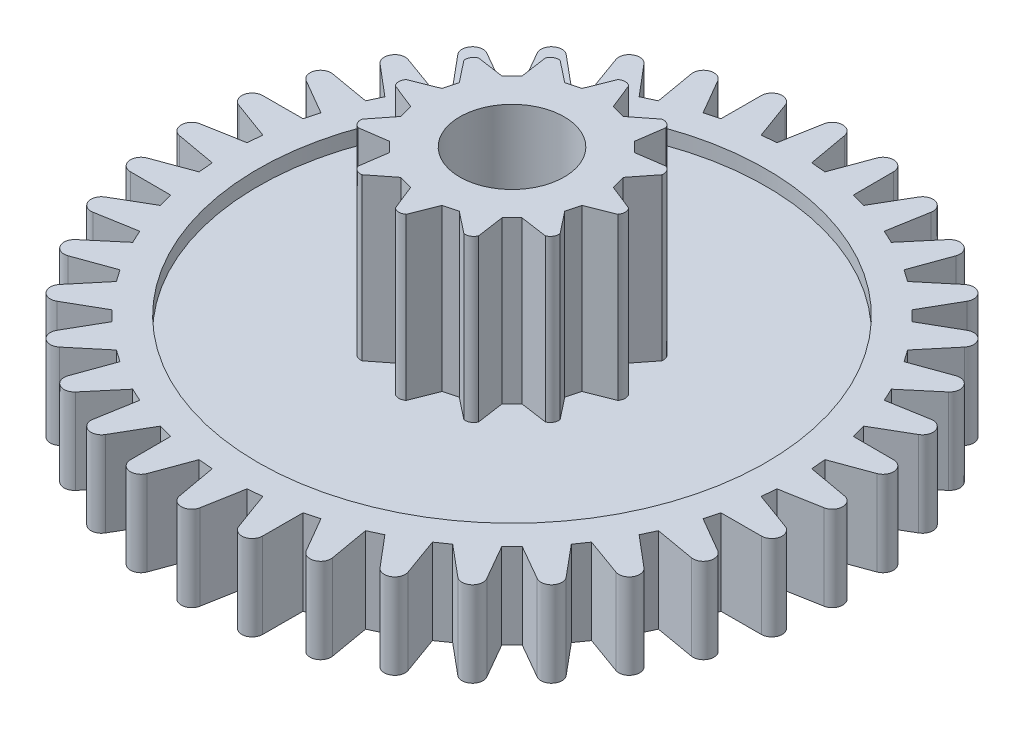
SolidWorks part; units mm, degrees
material "ABS"
ref_plane "Plano frontal" through (0, 0, 0) normal (0, 0, 1) x (1, 0, 0)
ref_plane "Plano superior" through (0, 0, 0) normal (0, 1, 0) x (1, 0, 0)
ref_plane "Plano direito" through (0, 0, 0) normal (1, 0, 0) x (0, 0, -1)
ref_plane "Plano1" through (0, -1.225, 0) normal (0, -1, 0) x (1, 0, 0)
sketch "Esboço1" plane through (0, -1.225, 0) normal (0, -1, 0) x (1, 0, 0)
  line L0 (-0.5, -8.1096) -> (-0.2953, -9.2529)
  line L1 (0.2953, -9.2529) -> (0.5, -8.1096)
  line L2 (0.5, -8.1096) -> (0.9158, -8.0732)
  line L3 (0.9158, -8.0732) -> (1.3159, -9.1636)
  line L4 (1.8976, -9.061) -> (1.9006, -7.8996)
  line L5 (1.9006, -7.8996) -> (2.3673, -7.9008)
  line L6 (2.3673, -7.9008) -> (2.8872, -8.7959)
  line L7 (3.4422, -8.5939) -> (3.2435, -7.4495)
  line L8 (3.2435, -7.4495) -> (3.6218, -7.2731)
  line L9 (3.6218, -7.2731) -> (4.3707, -8.1609)
  line L10 (4.8822, -7.8656) -> (4.4878, -6.7731)
  line L11 (4.4878, -6.7731) -> (4.8297, -6.5337)
  line L12 (4.8297, -6.5337) -> (5.7214, -7.2779)
  line L13 (6.1738, -6.8983) -> (5.5958, -5.8909)
  line L14 (5.5958, -5.8909) -> (5.8909, -5.5958)
  line L15 (5.8909, -5.5958) -> (6.8983, -6.1738)
  line L16 (7.2779, -5.7214) -> (6.5337, -4.8297)
  line L17 (6.5337, -4.8297) -> (6.7731, -4.4878)
  line L18 (6.7731, -4.4878) -> (7.8656, -4.8822)
  line L19 (8.1609, -4.3707) -> (7.2731, -3.6218)
  line L20 (7.2731, -3.6218) -> (7.4495, -3.2435)
  line L21 (7.4495, -3.2435) -> (8.5939, -3.4422)
  line L22 (8.7959, -2.8872) -> (7.9008, -2.3673)
  line L23 (7.9008, -2.3673) -> (7.8996, -1.9006)
  line L24 (7.8996, -1.9006) -> (9.061, -1.8976)
  line L25 (9.1636, -1.3159) -> (8.0732, -0.9158)
  line L26 (8.0732, -0.9158) -> (8.1096, -0.5)
  line L27 (8.1096, -0.5) -> (9.2529, -0.2953)
  line L28 (9.2529, 0.2953) -> (8.1096, 0.5)
  line L29 (8.1096, 0.5) -> (8.0732, 0.9158)
  line L30 (8.0732, 0.9158) -> (9.1636, 1.3159)
  line L31 (9.061, 1.8976) -> (7.8996, 1.9006)
  line L32 (7.8996, 1.9006) -> (7.9008, 2.3673)
  line L33 (7.9008, 2.3673) -> (8.7959, 2.8872)
  line L34 (8.5939, 3.4422) -> (7.4495, 3.2435)
  line L35 (7.4495, 3.2435) -> (7.2731, 3.6218)
  line L36 (7.2731, 3.6218) -> (8.1609, 4.3707)
  line L37 (7.8656, 4.8822) -> (6.7731, 4.4878)
  line L38 (6.7731, 4.4878) -> (6.5337, 4.8297)
  line L39 (6.5337, 4.8297) -> (7.2779, 5.7214)
  line L40 (6.8983, 6.1738) -> (5.8909, 5.5958)
  line L41 (5.8909, 5.5958) -> (5.5958, 5.8909)
  line L42 (5.5958, 5.8909) -> (6.1738, 6.8983)
  line L43 (5.7214, 7.2779) -> (4.8297, 6.5337)
  line L44 (4.8297, 6.5337) -> (4.4878, 6.7731)
  line L45 (4.4878, 6.7731) -> (4.8822, 7.8656)
  line L46 (4.3707, 8.1609) -> (3.6218, 7.2731)
  line L47 (3.6218, 7.2731) -> (3.2435, 7.4495)
  line L48 (3.2435, 7.4495) -> (3.4422, 8.5939)
  line L49 (2.8872, 8.7959) -> (2.3673, 7.9008)
  line L50 (2.3673, 7.9008) -> (1.9006, 7.8996)
  line L51 (1.9006, 7.8996) -> (1.8976, 9.061)
  line L52 (1.3159, 9.1636) -> (0.9158, 8.0732)
  line L53 (0.9158, 8.0732) -> (0.5, 8.1096)
  line L54 (0.5, 8.1096) -> (0.2953, 9.2529)
  line L55 (-0.2953, 9.2529) -> (-0.5, 8.1096)
  line L56 (-0.5, 8.1096) -> (-0.9158, 8.0732)
  line L57 (-0.9158, 8.0732) -> (-1.3159, 9.1636)
  line L58 (-1.8976, 9.061) -> (-1.9006, 7.8996)
  line L59 (-1.9006, 7.8996) -> (-2.3673, 7.9008)
  line L60 (-2.3673, 7.9008) -> (-2.8872, 8.7959)
  line L61 (-3.4422, 8.5939) -> (-3.2435, 7.4495)
  line L62 (-3.2435, 7.4495) -> (-3.6218, 7.2731)
  line L63 (-3.6218, 7.2731) -> (-4.3707, 8.1609)
  line L64 (-4.8822, 7.8656) -> (-4.4878, 6.7731)
  line L65 (-4.4878, 6.7731) -> (-4.8297, 6.5337)
  line L66 (-4.8297, 6.5337) -> (-5.7214, 7.2779)
  line L67 (-6.1738, 6.8983) -> (-5.5958, 5.8909)
  line L68 (-5.5958, 5.8909) -> (-5.8909, 5.5958)
  line L69 (-5.8909, 5.5958) -> (-6.8983, 6.1738)
  line L70 (-7.2779, 5.7214) -> (-6.5337, 4.8297)
  line L71 (-6.5337, 4.8297) -> (-6.7731, 4.4878)
  line L72 (-6.7731, 4.4878) -> (-7.8656, 4.8822)
  line L73 (-8.1609, 4.3707) -> (-7.2731, 3.6218)
  line L74 (-7.2731, 3.6218) -> (-7.4495, 3.2435)
  line L75 (-7.4495, 3.2435) -> (-8.5939, 3.4422)
  line L76 (-8.7959, 2.8872) -> (-7.9008, 2.3673)
  line L77 (-7.9008, 2.3673) -> (-7.8996, 1.9006)
  line L78 (-7.8996, 1.9006) -> (-9.061, 1.8976)
  line L79 (-9.1636, 1.3159) -> (-8.0732, 0.9158)
  line L80 (-8.0732, 0.9158) -> (-8.1096, 0.5)
  line L81 (-8.1096, 0.5) -> (-9.2529, 0.2953)
  line L82 (-9.2529, -0.2953) -> (-8.1096, -0.5)
  line L83 (-8.1096, -0.5) -> (-8.0732, -0.9158)
  line L84 (-8.0732, -0.9158) -> (-9.1636, -1.3159)
  line L85 (-9.061, -1.8976) -> (-7.8996, -1.9006)
  line L86 (-7.8996, -1.9006) -> (-7.9008, -2.3673)
  line L87 (-7.9008, -2.3673) -> (-8.7959, -2.8872)
  line L88 (-8.5939, -3.4422) -> (-7.4495, -3.2435)
  line L89 (-7.4495, -3.2435) -> (-7.2731, -3.6218)
  line L90 (-7.2731, -3.6218) -> (-8.1609, -4.3707)
  line L91 (-7.8656, -4.8822) -> (-6.7731, -4.4878)
  line L92 (-6.7731, -4.4878) -> (-6.5337, -4.8297)
  line L93 (-6.5337, -4.8297) -> (-7.2779, -5.7214)
  line L94 (-6.8983, -6.1738) -> (-5.8909, -5.5958)
  line L95 (-5.8909, -5.5958) -> (-5.5958, -5.8909)
  line L96 (-5.5958, -5.8909) -> (-6.1738, -6.8983)
  line L97 (-5.7214, -7.2779) -> (-4.8297, -6.5337)
  line L98 (-4.8297, -6.5337) -> (-4.4878, -6.7731)
  line L99 (-4.4878, -6.7731) -> (-4.8822, -7.8656)
  line L100 (-4.3707, -8.1609) -> (-3.6218, -7.2731)
  line L101 (-3.6218, -7.2731) -> (-3.2435, -7.4495)
  line L102 (-3.2435, -7.4495) -> (-3.4422, -8.5939)
  line L103 (-2.8872, -8.7959) -> (-2.3673, -7.9008)
  line L104 (-2.3673, -7.9008) -> (-1.9006, -7.8996)
  line L105 (-1.9006, -7.8996) -> (-1.8976, -9.061)
  line L106 (-1.3159, -9.1636) -> (-0.9158, -8.0732)
  line L107 (-0.9158, -8.0732) -> (-0.5, -8.1096)
  arc A0 (-0.2953, -9.2529) -> (0.2953, -9.2529) centre (0, -9.2) ccw
  arc A1 (1.3159, -9.1636) -> (1.8976, -9.061) centre (1.5976, -9.0602) ccw
  arc A2 (2.8872, -8.7959) -> (3.4422, -8.5939) centre (3.1466, -8.6452) ccw
  arc A3 (4.3707, -8.1609) -> (4.8822, -7.8656) centre (4.6, -7.9674) ccw
  arc A4 (5.7214, -7.2779) -> (6.1738, -6.8983) centre (5.9136, -7.0476) ccw
  arc A5 (6.8983, -6.1738) -> (7.2779, -5.7214) centre (7.0476, -5.9136) ccw
  arc A6 (7.8656, -4.8822) -> (8.1609, -4.3707) centre (7.9674, -4.6) ccw
  arc A7 (8.5939, -3.4422) -> (8.7959, -2.8872) centre (8.6452, -3.1466) ccw
  arc A8 (9.061, -1.8976) -> (9.1636, -1.3159) centre (9.0602, -1.5976) ccw
  arc A9 (9.2529, -0.2953) -> (9.2529, 0.2953) centre (9.2, 0) ccw
  arc A10 (9.1636, 1.3159) -> (9.061, 1.8976) centre (9.0602, 1.5976) ccw
  arc A11 (8.7959, 2.8872) -> (8.5939, 3.4422) centre (8.6452, 3.1466) ccw
  arc A12 (8.1609, 4.3707) -> (7.8656, 4.8822) centre (7.9674, 4.6) ccw
  arc A13 (7.2779, 5.7214) -> (6.8983, 6.1738) centre (7.0476, 5.9136) ccw
  arc A14 (6.1738, 6.8983) -> (5.7214, 7.2779) centre (5.9136, 7.0476) ccw
  arc A15 (4.8822, 7.8656) -> (4.3707, 8.1609) centre (4.6, 7.9674) ccw
  arc A16 (3.4422, 8.5939) -> (2.8872, 8.7959) centre (3.1466, 8.6452) ccw
  arc A17 (1.8976, 9.061) -> (1.3159, 9.1636) centre (1.5976, 9.0602) ccw
  arc A18 (0.2953, 9.2529) -> (-0.2953, 9.2529) centre (0, 9.2) ccw
  arc A19 (-1.3159, 9.1636) -> (-1.8976, 9.061) centre (-1.5976, 9.0602) ccw
  arc A20 (-2.8872, 8.7959) -> (-3.4422, 8.5939) centre (-3.1466, 8.6452) ccw
  arc A21 (-4.3707, 8.1609) -> (-4.8822, 7.8656) centre (-4.6, 7.9674) ccw
  arc A22 (-5.7214, 7.2779) -> (-6.1738, 6.8983) centre (-5.9136, 7.0476) ccw
  arc A23 (-6.8983, 6.1738) -> (-7.2779, 5.7214) centre (-7.0476, 5.9136) ccw
  arc A24 (-7.8656, 4.8822) -> (-8.1609, 4.3707) centre (-7.9674, 4.6) ccw
  arc A25 (-8.5939, 3.4422) -> (-8.7959, 2.8872) centre (-8.6452, 3.1466) ccw
  arc A26 (-9.061, 1.8976) -> (-9.1636, 1.3159) centre (-9.0602, 1.5976) ccw
  arc A27 (-9.2529, 0.2953) -> (-9.2529, -0.2953) centre (-9.2, 0) ccw
  arc A28 (-9.1636, -1.3159) -> (-9.061, -1.8976) centre (-9.0602, -1.5976) ccw
  arc A29 (-8.7959, -2.8872) -> (-8.5939, -3.4422) centre (-8.6452, -3.1466) ccw
  arc A30 (-8.1609, -4.3707) -> (-7.8656, -4.8822) centre (-7.9674, -4.6) ccw
  arc A31 (-7.2779, -5.7214) -> (-6.8983, -6.1738) centre (-7.0476, -5.9136) ccw
  arc A32 (-6.1738, -6.8983) -> (-5.7214, -7.2779) centre (-5.9136, -7.0476) ccw
  arc A33 (-4.8822, -7.8656) -> (-4.3707, -8.1609) centre (-4.6, -7.9674) ccw
  arc A34 (-3.4422, -8.5939) -> (-2.8872, -8.7959) centre (-3.1466, -8.6452) ccw
  arc A35 (-1.8976, -9.061) -> (-1.3159, -9.1636) centre (-1.5976, -9.0602) ccw
extrude "Ressalto-extrusão1" add sketch "Esboço1" against normal blind 2.45
hole_wizard "Furo com folga de M121" positions "Esboço3" profile "Esboço2" hole size "M12" standard "Ansi Metric"
sketch "Esboço3" plane through (0, 1.225, 0) normal (0, 1, 0) x (1, 0, 0)
  point P0 (0, 0)
sketch "Esboço2" plane through (0, 1.225, 0) normal (1, 0, 0) x (0, 0, 1)
  line L0 (0, 0) -> (0, 0.43)
  line L1 (0, 0.43) -> (7.3, 0.43)
  line L2 (7.3, 0.43) -> (7.3, 0)
  line L5 (7.3, 0) -> (0, 0)
  line L10 (0, 0.43) -> (-7.3, 0.43) construction
  line L11 (0, -6.35) -> (0, 107.95) construction
  dimension "Hole Dia." = 14.6
  dimension "Hole Depth" = 0.43
  dimension "Drill Angle" = 180
sketch "Esboço4" plane through (0, 0.795, 0) normal (0, 1, 0) x (-1, 0, 0)
  line L0 (-0.1557, -3.1956) -> (-0.5751, -2.1462)
  line L1 (-0.5751, -2.1462) -> (-1.463, -2.8453)
  line L2 (-1.7326, -2.6897) -> (-1.5711, -1.5711)
  line L3 (-1.5711, -1.5711) -> (-2.6897, -1.7326)
  line L4 (-2.8453, -1.463) -> (-2.1462, -0.5751)
  line L5 (-2.1462, -0.5751) -> (-3.1956, -0.1557)
  line L6 (-3.1956, 0.1557) -> (-2.1462, 0.5751)
  line L7 (-2.1462, 0.5751) -> (-2.8453, 1.463)
  line L8 (-2.6897, 1.7326) -> (-1.5711, 1.5711)
  line L9 (-1.5711, 1.5711) -> (-1.7326, 2.6897)
  line L10 (-1.463, 2.8453) -> (-0.5751, 2.1462)
  line L11 (-0.5751, 2.1462) -> (-0.1557, 3.1956)
  line L12 (0.1557, 3.1956) -> (0.5751, 2.1462)
  line L13 (0.5751, 2.1462) -> (1.463, 2.8453)
  line L14 (1.7326, 2.6897) -> (1.5711, 1.5711)
  line L15 (1.5711, 1.5711) -> (2.6897, 1.7326)
  line L16 (2.8453, 1.463) -> (2.1462, 0.5751)
  line L17 (2.1462, 0.5751) -> (3.1956, 0.1557)
  line L18 (3.1956, -0.1557) -> (2.1462, -0.5751)
  line L19 (2.1462, -0.5751) -> (2.8453, -1.463)
  line L20 (2.6897, -1.7326) -> (1.5711, -1.5711)
  line L21 (1.5711, -1.5711) -> (1.7326, -2.6897)
  line L22 (1.463, -2.8453) -> (0.5751, -2.1462)
  line L23 (0.5751, -2.1462) -> (0.1557, -3.1956)
  arc A0 (-1.463, -2.8453) -> (-1.7326, -2.6897) centre (-1.5, -2.5981) cw
  arc A1 (-2.6897, -1.7326) -> (-2.8453, -1.463) centre (-2.5981, -1.5) cw
  arc A2 (-3.1956, -0.1557) -> (-3.1956, 0.1557) centre (-3, 0) cw
  arc A3 (-2.8453, 1.463) -> (-2.6897, 1.7326) centre (-2.5981, 1.5) cw
  arc A4 (-1.7326, 2.6897) -> (-1.463, 2.8453) centre (-1.5, 2.5981) cw
  arc A5 (-0.1557, 3.1956) -> (0.1557, 3.1956) centre (0, 3) cw
  arc A6 (1.463, 2.8453) -> (1.7326, 2.6897) centre (1.5, 2.5981) cw
  arc A7 (2.6897, 1.7326) -> (2.8453, 1.463) centre (2.5981, 1.5) cw
  arc A8 (3.1956, 0.1557) -> (3.1956, -0.1557) centre (3, 0) cw
  arc A9 (2.8453, -1.463) -> (2.6897, -1.7326) centre (2.5981, -1.5) cw
  arc A10 (1.7326, -2.6897) -> (1.463, -2.8453) centre (1.5, -2.5981) cw
  arc A11 (0.1557, -3.1956) -> (-0.1557, -3.1956) centre (0, -3) cw
extrude "Ressalto-extrusão2" add sketch "Esboço4" along normal blind 4.63
hole_wizard "Furo com folga de M122" positions "Esboço6" profile "Esboço5" hole size "M12" standard "Ansi Metric"
sketch "Esboço6" plane through (0, -1.225, 0) normal (0, -1, 0) x (-1, 0, 0)
  point P0 (0, 0)
sketch "Esboço5" plane through (0, -1.225, 0) normal (1, 0, 0) x (0, 0, -1)
  line L0 (0, 0) -> (0, 0.43)
  line L1 (0, 0.43) -> (7.3, 0.43)
  line L2 (7.3, 0.43) -> (7.3, 0)
  line L5 (7.3, 0) -> (0, 0)
  line L10 (0, 0.43) -> (-7.3, 0.43) construction
  line L11 (0, -6.35) -> (0, 107.95) construction
  dimension "Hole Dia." = 14.6
  dimension "Hole Depth" = 0.43
  dimension "Drill Angle" = 180
draft "Inclinação1" type of draft neutral plane draft angle 15.151 faces to draft 1 face at (2.1339, 0, -7.9002) neutral plane through (1.8976, 1.225, -9.061) neutral plane normal (1, 0, -0.0026) parameters "D1"=15.151
draft "Inclinação2" type of draft neutral plane draft angle 15.151 faces to draft 1 face at (7.9002, 0, -2.1339) neutral plane through (7.8996, 1.225, -1.9006) neutral plane normal (0.0026, 0, -1) parameters "D1"=15.151
draft "Inclinação3" type of draft neutral plane draft angle 15.151 faces to draft 1 face at (7.9002, 0, 2.1339) neutral plane through (9.061, 1.225, 1.8976) neutral plane normal (0.0026, 0, 1) parameters "D1"=15.151
draft "Inclinação4" type of draft neutral plane draft angle 15.151 faces to draft 1 face at (2.1339, 0, 7.9002) neutral plane through (1.9006, 1.225, 7.8996) neutral plane normal (1, 0, 0.0026) parameters "D1"=15.151
draft "Inclinação5" type of draft neutral plane draft angle 15.151 faces to draft 1 face at (-2.1339, 0, 7.9002) neutral plane through (-1.8976, 1.225, 9.061) neutral plane normal (-1, 0, 0.0026) parameters "D1"=15.151
draft "Inclinação6" type of draft neutral plane draft angle 15.151 faces to draft 1 face at (-7.9002, 0, 2.1339) neutral plane through (-7.8996, 1.225, 1.9006) neutral plane normal (-0.0026, 0, 1) parameters "D1"=15.151
draft "Inclinação7" type of draft neutral plane draft angle 15.151 faces to draft 1 face at (-7.9002, 0, -2.1339) neutral plane through (-9.061, 1.225, -1.8976) neutral plane normal (-0.0026, 0, -1) parameters "D1"=15.151
draft "Inclinação8" type of draft neutral plane draft angle 15.151 faces to draft 1 face at (-2.1339, 0, -7.9002) neutral plane through (-1.9006, 1.225, -7.8996) neutral plane normal (-1, 0, -0.0026) parameters "D1"=15.151
ref_plane "Plano2" through (0, 0, 0) normal (0, 0, -1) x (-1, 0, 0)
sketch "Esboço7" plane through (0, 0, 0) normal (0, 0, -1) x (-1, 0, 0)
  line L0 (-2.5, -1.225) -> (0, -1.225)
  line L1 (0, -1.225) -> (0, -0.795)
  line L2 (0, -0.795) -> (-2.5, -0.795)
  line L3 (-2.5, -0.795) -> (-2.5, -1.225)
  line L4 (0, -1.225) -> (0, -0.795) construction
revolve "Revolução1" add sketch "Esboço7" angle 360 about L4
hole_wizard "Furo de diâmetro Ø3.0 (3)1" positions "Esboço9" profile "Esboço8" hole size "Ø3.0" standard "Ansi Metric"
sketch "Esboço9" plane through (0, 5.425, 0) normal (0, 1, 0) x (1, 0, 0)
  point P0 (0, 0)
sketch "Esboço8" plane through (0, 5.425, 0) normal (1, 0, 0) x (0, 0, 1)
  line L0 (0, 0) -> (0, 6.65)
  line L1 (0, 6.65) -> (1.5, 6.65)
  line L2 (1.5, 6.65) -> (1.5, 0)
  line L5 (1.5, 0) -> (0, 0)
  line L11 (0, -6.35) -> (0, 107.95) construction
  dimension "Thru Hole Dia." = 3
  dimension "Thru Hole Depth" = 6.65
chamfer "Chanfro1" distance 0.337 angle 53.215 12 edges at (-1.5711, 3.11, 1.5711) (-0.5751, 3.11, -2.1462) (-2.1462, 3.11, -0.5751) (1.5711, 3.11, -1.5711) (-0.5751, 3.11, 2.1462) (2.1462, 3.11, -0.5751) (-2.1462, 3.11, 0.5751) (2.1462, 3.11, 0.5751) (-1.5711, 3.11, -1.5711) (1.5711, 3.11, 1.5711) (0.5751, 3.11, -2.1462) (0.5751, 3.11, 2.1462)
